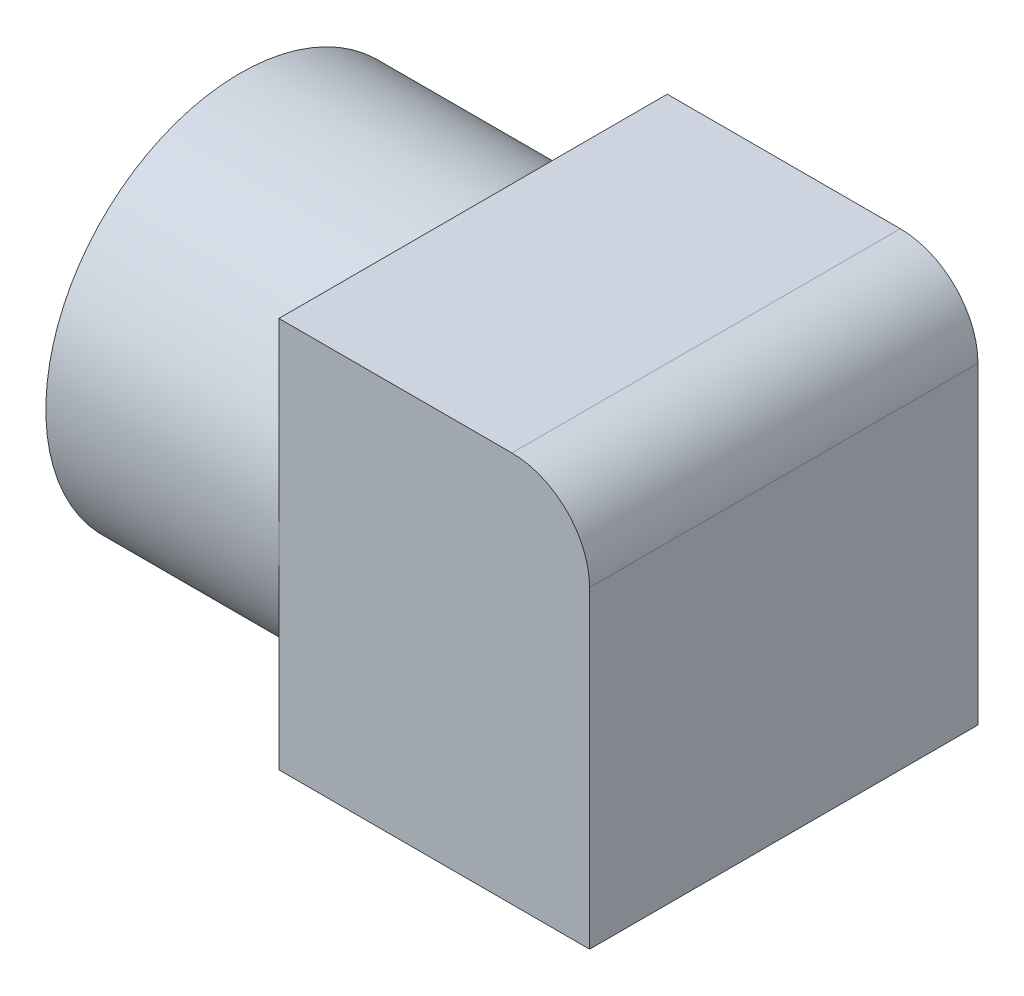
SolidWorks part; units mm, degrees
ref_plane "Front Plane" through (0, 0, 0) normal (0, 0, 1) x (1, 0, 0)
ref_plane "Top Plane" through (0, 0, 0) normal (0, 1, 0) x (1, 0, 0)
ref_plane "Right Plane" through (0, 0, 0) normal (1, 0, 0) x (0, 0, -1)
sketch "Sketch1" plane through (0, 0, 0) normal (1, 0, 0) x (0, 0, -1)
  circle A0 centre (0, 0) radius 25
  dimension "D1" = 50
extrude "Boss-Extrude1" add sketch "Sketch1" along normal blind 30
sketch "Sketch2" plane through (30, 0, 0) normal (1, 0, 0) x (0, 0, -1)
  line L1 (-25, 25.1637) -> (25, 25.1637)
  line L2 (-25, 25.1637) -> (-25, -25.1637)
  line L3 (-25, -25.1637) -> (25, -25.1637)
  line L4 (25, 25.1637) -> (25, -25.1637)
  line L5 (-25, 25.1637) -> (25, -25.1637) construction
  line L6 (-25, -25.1637) -> (25, 25.1637) construction
  point P0 (0, 0)
  dimension "D1" = 50
extrude "Boss-Extrude2" add sketch "Sketch2" along normal blind 40
fillet "Fillet1" radius 10 1 edges at (70, 25.1637, 0)
sketch "Sketch3" plane through (0, -25.1637, 0) normal (0, -1, 0) x (1, 0, 0)
  line L0 (30, 25) -> (70, -25) construction
  circle A0 centre (50, 0) radius 15
  dimension "D1" = 30
extrude "Cut-Extrude1" cut sketch "Sketch3" against normal blind 10
